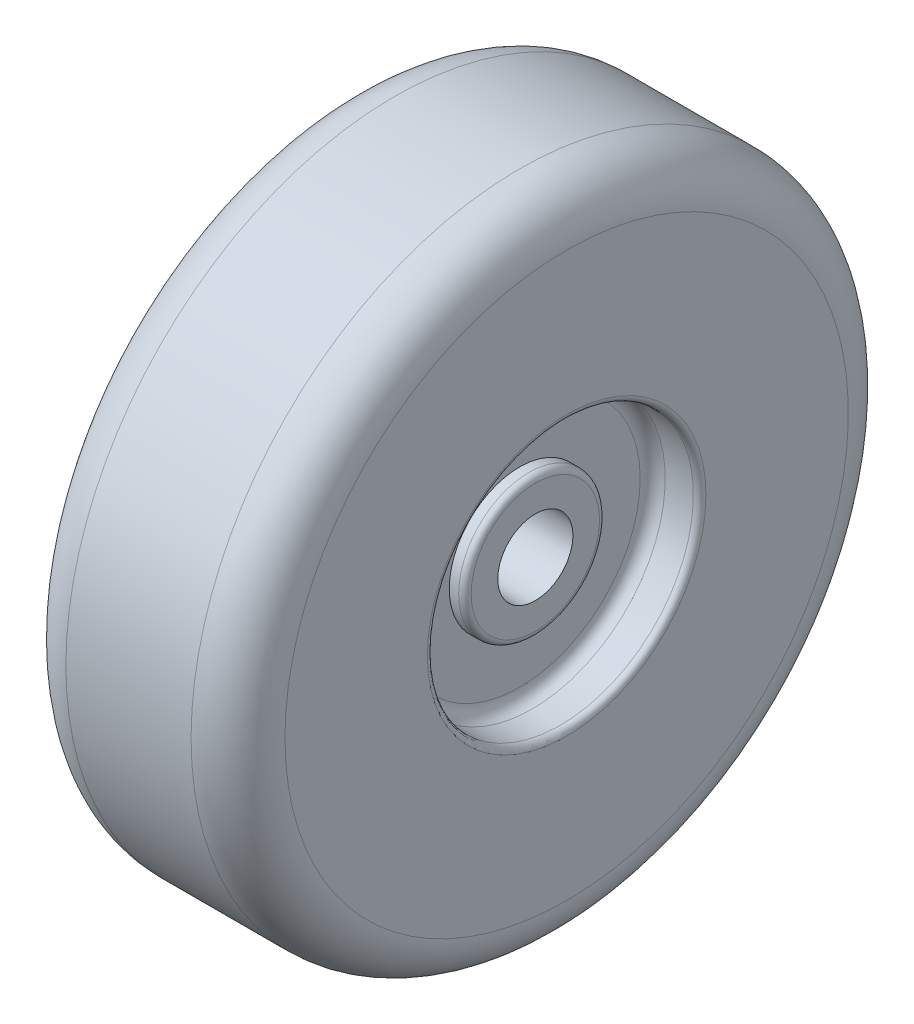
SolidWorks part; units mm, degrees
ref_plane "Plano frontal" through (0, 0, 0) normal (0, 0, 1) x (1, 0, 0)
ref_plane "Plano superior" through (0, 0, 0) normal (0, 1, 0) x (1, 0, 0)
ref_plane "Plano direito" through (0, 0, 0) normal (1, 0, 0) x (0, 0, -1)
sketch "Esboço1" plane through (0, 0, 0) normal (1, 0, 0) x (0, 0, -1)
  circle A0 centre (0, 0) radius 10.5
  circle A1 centre (0, 0) radius 1.75
  circle A2 centre (0, 0) radius 5.25
  dimension "D1" = 21
  dimension "D2" = 10.5
  dimension "D3" = 3.5
sketch "Esboço6" plane through (0, 0, 0) normal (0, 0, 1) x (1, 0, 0)
  line L0 (0, 0) -> (10.1982, 0) construction
  line L1 (2.5, 1.2) -> (2.5, 2.05)
  line L3 (0, 1.15) -> (0, 11.6959) construction
  line L4 (2.3, 2.25) -> (2, 2.25)
  line L10 (-2, 10.5) -> (2, 10.5)
  line L11 (3.5, 9) -> (3.5, 4.45)
  line L17 (3.3, 4.25) -> (2.4, 4.25)
  line L18 (2, 3.85) -> (2, 2.25)
  line L25 (-2, 3.85) -> (-2, 2.25)
  line L26 (-3.3, 4.25) -> (-2.4, 4.25)
  line L27 (-3.5, 9) -> (-3.5, 4.45)
  line L29 (-2.3, 2.25) -> (-2, 2.25)
  line L30 (-2.5, 1.2) -> (-2.5, 2.05)
  line L32 (-2.5, 1.2) -> (2.5, 1.2)
  arc A0 (2, 10.5) -> (3.5, 9) centre (2, 9) cw
  arc A1 (2.4, 4.25) -> (2, 3.85) centre (2.4, 3.85) ccw
  arc A4 (2.5, 2.05) -> (2.3, 2.25) centre (2.3, 2.05) ccw
  arc A10 (-2.5, 2.05) -> (-2.3, 2.25) centre (-2.3, 2.05) cw
  arc A13 (-2.4, 4.25) -> (-2, 3.85) centre (-2.4, 3.85) cw
  arc A14 (-2, 10.5) -> (-3.5, 9) centre (-2, 9) ccw
  arc A15 (3.5, 4.45) -> (3.3, 4.25) centre (3.3, 4.45) cw
  arc A16 (-3.5, 4.45) -> (-3.3, 4.25) centre (-3.3, 4.45) ccw
  point P5 (0, 1.75)
  point P6 (0, 5.25)
  point P7 (0, 10.5)
  point P20 (3.5, 10.5)
  point P51 (0, 10.5)
  dimension "D2" = 1.5
  dimension "D6" = 0.4
  dimension "D9" = 0.2
  dimension "D3" = 0.2
  dimension "D1" = 2
  dimension "D8" = 0.5
  dimension "D10" = 1.2
revolve "Revolução2" add sketch "Esboço6" angle 360 about L0
